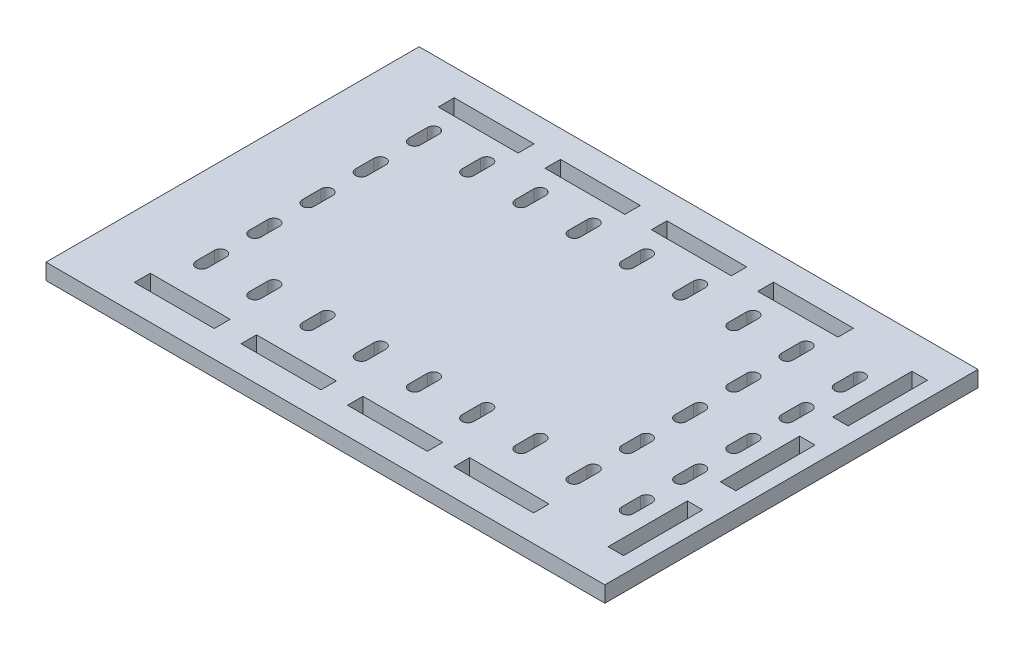
SolidWorks part; units mm, degrees
ref_plane "Front Plane" through (0, 0, 0) normal (0, 0, 1) x (1, 0, 0)
ref_plane "Top Plane" through (0, 0, 0) normal (0, 1, 0) x (1, 0, 0)
ref_plane "Right Plane" through (0, 0, 0) normal (1, 0, 0) x (0, 0, -1)
sketch "Sketch1" plane through (0, 0, 0) normal (0, 1, 0) x (1, 0, 0)
  line L1 (0, 0) -> (200, 0)
  line L2 (0, 0) -> (0, 140.2)
  line L3 (0, 140.2) -> (200, 140.2)
  line L4 (200, 0) -> (200, 140.2)
  line L5 (0, 0) -> (200, 140.2) construction
  line L6 (0, 140.2) -> (200, 0) construction
  point P4 (100, 70.1)
  dimension "D1" = 200
  dimension "D2" = 140.2
extrude "Boss-Extrude1" add sketch "Sketch1" along normal blind 6
sketch "Sketch2" plane through (0, 6, 0) normal (0, 1, 0) x (1, 0, 0)
  line L0 (188.2, 127.2) -> (194, 127.2)
  line L1 (188.2, 127.2) -> (188.2, 97.4)
  line L2 (188.2, 97.4) -> (194, 97.4)
  line L3 (194, 127.2) -> (194, 97.4)
  line L4 (188.2, 127.2) -> (194, 97.4) construction
  line L5 (188.2, 97.4) -> (194, 127.2) construction
  line L6 (188.2, 85) -> (194, 85)
  line L7 (188.2, 85) -> (188.2, 55.2)
  line L8 (188.2, 55.2) -> (194, 55.2)
  line L9 (194, 85) -> (194, 55.2)
  line L10 (188.2, 85) -> (194, 55.2) construction
  line L11 (188.2, 55.2) -> (194, 85) construction
  line L12 (188.2, 42.8) -> (194, 42.8)
  line L13 (188.2, 42.8) -> (188.2, 13)
  line L14 (188.2, 13) -> (194, 13)
  line L15 (194, 42.8) -> (194, 13)
  line L16 (188.2, 42.8) -> (194, 13) construction
  line L17 (188.2, 13) -> (194, 42.8) construction
  line L19 (200, 140.2) -> (0, 140.2) construction
  line L22 (0, 0) -> (200, 0) construction
  line L23 (200, 0) -> (200, 140.2) construction
  point P4 (191.1, 112.3)
  point P9 (191.1, 70.1)
  point P14 (191.1, 27.9)
  dimension "D1" = 13
  dimension "D2" = 29.8
  dimension "D3" = 29.8
  dimension "D4" = 13
  dimension "D5" = 0
  dimension "D6" = 12.4
  dimension "D7" = 0
  dimension "D8" = 29.8
  dimension "D9" = 12.4
  dimension "D10" = 6
  dimension "D11" = 5.8
  dimension "D12" = 5.8
  dimension "D13" = 5.8
extrude "Cut-Extrude1" cut sketch "Sketch2" against normal blind 6
sketch "Sketch5" plane through (0, 6, 0) normal (0, 1, 0) x (1, 0, 0)
  line L0 (53.2, 130.1) -> (83.2, 130.1)
  line L1 (133.2, 124.2) -> (163.2, 124.4)
  line L2 (163.2, 124.4) -> (163.2, 130.2)
  line L3 (163.2, 130.2) -> (133.2, 130.2)
  line L4 (133.2, 130.2) -> (133.2, 124.2)
  line L5 (93.2, 124.3) -> (123.2, 124.3)
  line L6 (123.2, 124.3) -> (123.2, 130.1)
  line L7 (123.2, 130.1) -> (93.2, 130.1)
  line L8 (93.2, 130.1) -> (93.2, 124.3)
  line L10 (83.2, 124.3) -> (83.2, 130.1)
  line L12 (53.2, 124.3) -> (53.2, 130.1)
  line L13 (13.2, 124.2) -> (43.2, 124.2)
  line L14 (43.2, 124.2) -> (43.2, 130.2)
  line L15 (43.2, 130.2) -> (13.2, 130.2)
  line L16 (13.2, 130.2) -> (13.2, 124.2)
  line L17 (148.2, 130.2) -> (188.2, 130.2) construction
  line L18 (188.2, 127.2) -> (188.2, 130.2)
  line L19 (83.2, 124.3) -> (53.2, 124.3)
  line L20 (200, 140.2) -> (0, 140.2) construction
  line L21 (53.2, 15.9) -> (83.2, 15.9)
  line L22 (200, 70.1) -> (0, 70.1) construction
  line L23 (200, 0) -> (200, 140.2) construction
  line L24 (0, 140.2) -> (0, 0) construction
  line L25 (13.2, 10) -> (13.2, 16)
  line L26 (43.2, 10) -> (13.2, 10)
  line L27 (43.2, 16) -> (43.2, 10)
  line L28 (13.2, 16) -> (43.2, 16)
  line L29 (53.2, 15.9) -> (53.2, 10.1)
  line L31 (83.2, 15.9) -> (83.2, 10.1)
  line L33 (93.2, 10.1) -> (93.2, 15.9)
  line L34 (123.2, 10.1) -> (93.2, 10.1)
  line L35 (123.2, 15.9) -> (123.2, 10.1)
  line L36 (93.2, 15.9) -> (123.2, 15.9)
  line L37 (133.2, 10) -> (133.2, 16)
  line L38 (163.2, 10) -> (133.2, 10)
  line L39 (163.2, 15.8) -> (163.2, 10)
  line L40 (133.2, 16) -> (163.2, 15.8)
  line L41 (83.2, 10.1) -> (53.2, 10.1)
  point P1 (83.2, 127.2)
  point P21 (133.2, 127.2)
  point P23 (123.2, 127.2)
  point P24 (93.2, 127.2)
  point P27 (53.2, 127.2)
  point P28 (43.2, 127.2)
  dimension "D2" = 30
  dimension "D3" = 30
  dimension "D4" = 30
  dimension "D5" = 30
  dimension "D6" = 10
  dimension "D7" = 10
  dimension "D8" = 10
  dimension "D9" = 40
  dimension "D10" = 13
  dimension "D11" = 13
  dimension "D12" = 5.8
  dimension "D13" = 5.8
  dimension "D14" = 5.8
  dimension "D15" = 6
  dimension "D16" = 13
  dimension "D17" = 13
  dimension "D18" = 5.8
  dimension "D19" = 13
  dimension "D20" = 5.8
extrude "Cut-Extrude3" cut sketch "Sketch5" against normal blind 6 contours L15 L16 L13 L14 | L19 L10 L0 L12 | L7 L8 L5 L6 | L3 L4 L1 L2 | L40 L37 L38 L39 | L36 L33 L34 L35 | L41 L31 L21 L29 | L28 L25 L26 L27
sketch "Sketch6" plane through (0, 6, 0) normal (0, 1, 0) x (1, 0, 0)
  line L0 (200, 0) -> (200, 140.2) construction
  line L2 (182.2, 68.5311) -> (182.2, 75.5311)
  line L3 (177.8, 68.5304) -> (177.8, 75.5304)
  line L4 (162.2, 68.5304) -> (162.2, 75.5304)
  line L5 (157.8, 68.5304) -> (157.8, 75.5304)
  line L6 (182.2, 48.5311) -> (182.2, 55.5311)
  line L7 (177.8, 48.5304) -> (177.8, 55.5304)
  line L8 (162.2, 48.5304) -> (162.2, 55.5304)
  line L9 (182.2, 88.5311) -> (182.2, 95.5311)
  line L10 (177.8, 88.5304) -> (177.8, 95.5304)
  line L11 (182.2, 108.531) -> (182.2, 115.531)
  line L12 (177.8, 108.5313) -> (177.8, 115.5313)
  line L13 (162.2, 108.5304) -> (162.2, 115.5304)
  line L14 (157.8, 108.5304) -> (157.8, 115.5304)
  line L15 (162.2, 88.5304) -> (162.2, 95.5304)
  line L16 (157.8, 88.5304) -> (157.8, 95.5304)
  line L17 (157.8, 48.5304) -> (157.8, 55.5304)
  line L18 (182.2, 28.5311) -> (182.2, 35.5311)
  line L19 (177.8, 28.5304) -> (177.8, 35.5304)
  line L20 (162.2, 28.5304) -> (162.2, 35.5304)
  line L21 (157.8, 28.5304) -> (157.8, 35.5304)
  line L24 (142.2, 108.5304) -> (142.2, 115.5304)
  line L25 (137.8, 108.5304) -> (137.8, 115.5304)
  line L29 (142.2, 28.5304) -> (142.2, 35.5304)
  line L30 (137.8, 28.5304) -> (137.8, 35.5304)
  line L34 (122.2, 108.5304) -> (122.2, 115.5304)
  line L35 (117.8, 108.5304) -> (117.8, 115.5304)
  line L39 (122.2, 28.5304) -> (122.2, 35.5304)
  line L40 (117.8, 28.5304) -> (117.8, 35.5304)
  line L44 (102.2, 108.5304) -> (102.2, 115.5304)
  line L45 (97.8, 108.5304) -> (97.8, 115.5304)
  line L49 (102.2, 28.5304) -> (102.2, 35.5304)
  line L50 (97.8, 28.5304) -> (97.8, 35.5304)
  line L54 (82.2, 108.5304) -> (82.2, 115.5304)
  line L55 (77.8, 108.5304) -> (77.8, 115.5304)
  line L59 (82.2, 28.5304) -> (82.2, 35.5304)
  line L60 (77.8, 28.5304) -> (77.8, 35.5304)
  line L64 (62.2, 108.5304) -> (62.2, 115.5304)
  line L65 (57.8, 108.5304) -> (57.8, 115.5304)
  line L69 (62.2, 28.5304) -> (62.2, 35.5304)
  line L70 (57.8, 28.5304) -> (57.8, 35.5304)
  line L74 (42.2, 108.5304) -> (42.2, 115.5304)
  line L75 (37.8, 108.5304) -> (37.8, 115.5304)
  line L79 (42.2, 28.5304) -> (42.2, 35.5304)
  line L80 (37.8, 28.5304) -> (37.8, 35.5304)
  line L81 (22.2, 68.5304) -> (22.2, 75.5304)
  line L82 (17.8, 68.5304) -> (17.8, 75.5304)
  line L83 (22.2, 48.5304) -> (22.2, 55.5304)
  line L84 (22.2, 108.5304) -> (22.2, 115.5304)
  line L85 (17.8, 108.5304) -> (17.8, 115.5304)
  line L86 (22.2, 88.5304) -> (22.2, 95.5304)
  line L87 (17.8, 88.5304) -> (17.8, 95.5304)
  line L88 (17.8, 48.5304) -> (17.8, 55.5304)
  line L89 (22.2, 28.5304) -> (22.2, 35.5304)
  line L90 (17.8, 28.5304) -> (17.8, 35.5304)
  line L91 (142.2, 68.5304) -> (142.2, 75.5304) [skipped]
  line L92 (137.8, 68.5304) -> (137.8, 75.5304) [skipped]
  line L93 (142.2, 48.5304) -> (142.2, 55.5304) [skipped]
  line L94 (142.2, 88.5304) -> (142.2, 95.5304) [skipped]
  line L95 (137.8, 88.5304) -> (137.8, 95.5304) [skipped]
  line L96 (137.8, 48.5304) -> (137.8, 55.5304) [skipped]
  line L97 (122.2, 68.5304) -> (122.2, 75.5304) [skipped]
  line L98 (117.8, 68.5304) -> (117.8, 75.5304) [skipped]
  line L99 (122.2, 48.5304) -> (122.2, 55.5304) [skipped]
  line L100 (122.2, 88.5304) -> (122.2, 95.5304) [skipped]
  line L101 (117.8, 88.5304) -> (117.8, 95.5304) [skipped]
  line L102 (117.8, 48.5304) -> (117.8, 55.5304) [skipped]
  line L103 (102.2, 68.5304) -> (102.2, 75.5304) [skipped]
  line L104 (97.8, 68.5304) -> (97.8, 75.5304) [skipped]
  line L105 (102.2, 48.5304) -> (102.2, 55.5304) [skipped]
  line L106 (102.2, 88.5304) -> (102.2, 95.5304) [skipped]
  line L107 (97.8, 88.5304) -> (97.8, 95.5304) [skipped]
  line L108 (97.8, 48.5304) -> (97.8, 55.5304) [skipped]
  line L109 (82.2, 68.5304) -> (82.2, 75.5304) [skipped]
  line L110 (77.8, 68.5304) -> (77.8, 75.5304) [skipped]
  line L111 (82.2, 48.5304) -> (82.2, 55.5304) [skipped]
  line L112 (82.2, 88.5304) -> (82.2, 95.5304) [skipped]
  line L113 (77.8, 88.5304) -> (77.8, 95.5304) [skipped]
  line L114 (77.8, 48.5304) -> (77.8, 55.5304) [skipped]
  line L115 (62.2, 68.5304) -> (62.2, 75.5304) [skipped]
  line L116 (57.8, 68.5304) -> (57.8, 75.5304) [skipped]
  line L117 (62.2, 48.5304) -> (62.2, 55.5304) [skipped]
  line L118 (62.2, 88.5304) -> (62.2, 95.5304) [skipped]
  line L119 (57.8, 88.5304) -> (57.8, 95.5304) [skipped]
  line L120 (57.8, 48.5304) -> (57.8, 55.5304) [skipped]
  line L121 (42.2, 68.5304) -> (42.2, 75.5304) [skipped]
  line L122 (37.8, 68.5304) -> (37.8, 75.5304) [skipped]
  line L123 (42.2, 48.5304) -> (42.2, 55.5304) [skipped]
  line L124 (42.2, 88.5304) -> (42.2, 95.5304) [skipped]
  line L125 (37.8, 88.5304) -> (37.8, 95.5304) [skipped]
  line L126 (37.8, 48.5304) -> (37.8, 55.5304) [skipped]
  arc A0 (177.8, 68.5304) -> (182.2, 68.5311) centre (180, 68.5308) ccw
  arc A1 (182.2, 75.5311) -> (177.8, 75.5304) centre (180, 75.5311) ccw
  arc A2 (157.8, 68.5304) -> (162.2, 68.5304) centre (160, 68.5304) ccw
  arc A3 (162.2, 75.5304) -> (157.8, 75.5304) centre (160, 75.5304) ccw
  arc A4 (177.8, 48.5304) -> (182.2, 48.5311) centre (180, 48.5308) ccw
  arc A5 (182.2, 55.5311) -> (177.8, 55.5304) centre (180, 55.5311) ccw
  arc A6 (157.8, 48.5304) -> (162.2, 48.5304) centre (160, 48.5304) ccw
  arc A7 (162.2, 55.5304) -> (157.8, 55.5304) centre (160, 55.5304) ccw
  arc A8 (177.8, 88.5304) -> (182.2, 88.5311) centre (180, 88.5308) ccw
  arc A9 (182.2, 95.5311) -> (177.8, 95.5304) centre (180, 95.5311) ccw
  arc A10 (177.8, 108.5313) -> (182.2, 108.531) centre (180, 108.5311) ccw
  arc A11 (182.2, 115.531) -> (177.8, 115.5313) centre (180, 115.531) ccw
  arc A12 (162.2, 115.5304) -> (157.8, 115.5304) centre (160, 115.5304) ccw
  arc A13 (157.8, 108.5304) -> (162.2, 108.5304) centre (160, 108.5304) ccw
  arc A14 (157.8, 88.5304) -> (162.2, 88.5304) centre (160, 88.5304) ccw
  arc A15 (162.2, 95.5304) -> (157.8, 95.5304) centre (160, 95.5304) ccw
  arc A16 (177.8, 28.5304) -> (182.2, 28.5311) centre (180, 28.5308) ccw
  arc A17 (182.2, 35.5311) -> (177.8, 35.5304) centre (180, 35.5311) ccw
  arc A18 (157.8, 28.5304) -> (162.2, 28.5304) centre (160, 28.5304) ccw
  arc A19 (162.2, 35.5304) -> (157.8, 35.5304) centre (160, 35.5304) ccw
  arc A24 (142.2, 115.5304) -> (137.8, 115.5304) centre (140, 115.5304) ccw
  arc A25 (137.8, 108.5304) -> (142.2, 108.5304) centre (140, 108.5304) ccw
  arc A28 (137.8, 28.5304) -> (142.2, 28.5304) centre (140, 28.5304) ccw
  arc A29 (142.2, 35.5304) -> (137.8, 35.5304) centre (140, 35.5304) ccw
  arc A34 (122.2, 115.5304) -> (117.8, 115.5304) centre (120, 115.5304) ccw
  arc A35 (117.8, 108.5304) -> (122.2, 108.5304) centre (120, 108.5304) ccw
  arc A38 (117.8, 28.5304) -> (122.2, 28.5304) centre (120, 28.5304) ccw
  arc A39 (122.2, 35.5304) -> (117.8, 35.5304) centre (120, 35.5304) ccw
  arc A44 (102.2, 115.5304) -> (97.8, 115.5304) centre (100, 115.5304) ccw
  arc A45 (97.8, 108.5304) -> (102.2, 108.5304) centre (100, 108.5304) ccw
  arc A48 (97.8, 28.5304) -> (102.2, 28.5304) centre (100, 28.5304) ccw
  arc A49 (102.2, 35.5304) -> (97.8, 35.5304) centre (100, 35.5304) ccw
  arc A54 (82.2, 115.5304) -> (77.8, 115.5304) centre (80, 115.5304) ccw
  arc A55 (77.8, 108.5304) -> (82.2, 108.5304) centre (80, 108.5304) ccw
  arc A58 (77.8, 28.5304) -> (82.2, 28.5304) centre (80, 28.5304) ccw
  arc A59 (82.2, 35.5304) -> (77.8, 35.5304) centre (80, 35.5304) ccw
  arc A64 (62.2, 115.5304) -> (57.8, 115.5304) centre (60, 115.5304) ccw
  arc A65 (57.8, 108.5304) -> (62.2, 108.5304) centre (60, 108.5304) ccw
  arc A68 (57.8, 28.5304) -> (62.2, 28.5304) centre (60, 28.5304) ccw
  arc A69 (62.2, 35.5304) -> (57.8, 35.5304) centre (60, 35.5304) ccw
  arc A74 (42.2, 115.5304) -> (37.8, 115.5304) centre (40, 115.5304) ccw
  arc A75 (37.8, 108.5304) -> (42.2, 108.5304) centre (40, 108.5304) ccw
  arc A78 (37.8, 28.5304) -> (42.2, 28.5304) centre (40, 28.5304) ccw
  arc A79 (42.2, 35.5304) -> (37.8, 35.5304) centre (40, 35.5304) ccw
  arc A80 (17.8, 68.5304) -> (22.2, 68.5304) centre (20, 68.5304) ccw
  arc A81 (22.2, 75.5304) -> (17.8, 75.5304) centre (20, 75.5304) ccw
  arc A82 (17.8, 48.5304) -> (22.2, 48.5304) centre (20, 48.5304) ccw
  arc A83 (22.2, 55.5304) -> (17.8, 55.5304) centre (20, 55.5304) ccw
  arc A84 (22.2, 115.5304) -> (17.8, 115.5304) centre (20, 115.5304) ccw
  arc A85 (17.8, 108.5304) -> (22.2, 108.5304) centre (20, 108.5304) ccw
  arc A86 (17.8, 88.5304) -> (22.2, 88.5304) centre (20, 88.5304) ccw
  arc A87 (22.2, 95.5304) -> (17.8, 95.5304) centre (20, 95.5304) ccw
  arc A88 (17.8, 28.5304) -> (22.2, 28.5304) centre (20, 28.5304) ccw
  arc A89 (22.2, 35.5304) -> (17.8, 35.5304) centre (20, 35.5304) ccw
  arc A90 (137.8, 68.5304) -> (142.2, 68.5304) centre (140, 68.5304) ccw [skipped]
  arc A91 (142.2, 75.5304) -> (137.8, 75.5304) centre (140, 75.5304) ccw [skipped]
  arc A92 (137.8, 48.5304) -> (142.2, 48.5304) centre (140, 48.5304) ccw [skipped]
  arc A93 (142.2, 55.5304) -> (137.8, 55.5304) centre (140, 55.5304) ccw [skipped]
  arc A94 (137.8, 88.5304) -> (142.2, 88.5304) centre (140, 88.5304) ccw [skipped]
  arc A95 (142.2, 95.5304) -> (137.8, 95.5304) centre (140, 95.5304) ccw [skipped]
  arc A96 (117.8, 68.5304) -> (122.2, 68.5304) centre (120, 68.5304) ccw [skipped]
  arc A97 (122.2, 75.5304) -> (117.8, 75.5304) centre (120, 75.5304) ccw [skipped]
  arc A98 (117.8, 48.5304) -> (122.2, 48.5304) centre (120, 48.5304) ccw [skipped]
  arc A99 (122.2, 55.5304) -> (117.8, 55.5304) centre (120, 55.5304) ccw [skipped]
  arc A100 (117.8, 88.5304) -> (122.2, 88.5304) centre (120, 88.5304) ccw [skipped]
  arc A101 (122.2, 95.5304) -> (117.8, 95.5304) centre (120, 95.5304) ccw [skipped]
  arc A102 (97.8, 68.5304) -> (102.2, 68.5304) centre (100, 68.5304) ccw [skipped]
  arc A103 (102.2, 75.5304) -> (97.8, 75.5304) centre (100, 75.5304) ccw [skipped]
  arc A104 (97.8, 48.5304) -> (102.2, 48.5304) centre (100, 48.5304) ccw [skipped]
  arc A105 (102.2, 55.5304) -> (97.8, 55.5304) centre (100, 55.5304) ccw [skipped]
  arc A106 (97.8, 88.5304) -> (102.2, 88.5304) centre (100, 88.5304) ccw [skipped]
  arc A107 (102.2, 95.5304) -> (97.8, 95.5304) centre (100, 95.5304) ccw [skipped]
  arc A108 (77.8, 68.5304) -> (82.2, 68.5304) centre (80, 68.5304) ccw [skipped]
  arc A109 (82.2, 75.5304) -> (77.8, 75.5304) centre (80, 75.5304) ccw [skipped]
  arc A110 (77.8, 48.5304) -> (82.2, 48.5304) centre (80, 48.5304) ccw [skipped]
  arc A111 (82.2, 55.5304) -> (77.8, 55.5304) centre (80, 55.5304) ccw [skipped]
  arc A112 (77.8, 88.5304) -> (82.2, 88.5304) centre (80, 88.5304) ccw [skipped]
  arc A113 (82.2, 95.5304) -> (77.8, 95.5304) centre (80, 95.5304) ccw [skipped]
  arc A114 (57.8, 68.5304) -> (62.2, 68.5304) centre (60, 68.5304) ccw [skipped]
  arc A115 (62.2, 75.5304) -> (57.8, 75.5304) centre (60, 75.5304) ccw [skipped]
  arc A116 (57.8, 48.5304) -> (62.2, 48.5304) centre (60, 48.5304) ccw [skipped]
  arc A117 (62.2, 55.5304) -> (57.8, 55.5304) centre (60, 55.5304) ccw [skipped]
  arc A118 (57.8, 88.5304) -> (62.2, 88.5304) centre (60, 88.5304) ccw [skipped]
  arc A119 (62.2, 95.5304) -> (57.8, 95.5304) centre (60, 95.5304) ccw [skipped]
  arc A120 (37.8, 68.5304) -> (42.2, 68.5304) centre (40, 68.5304) ccw [skipped]
  arc A121 (42.2, 75.5304) -> (37.8, 75.5304) centre (40, 75.5304) ccw [skipped]
  arc A122 (37.8, 48.5304) -> (42.2, 48.5304) centre (40, 48.5304) ccw [skipped]
  arc A123 (42.2, 55.5304) -> (37.8, 55.5304) centre (40, 55.5304) ccw [skipped]
  arc A124 (37.8, 88.5304) -> (42.2, 88.5304) centre (40, 88.5304) ccw [skipped]
  arc A125 (42.2, 95.5304) -> (37.8, 95.5304) centre (40, 95.5304) ccw [skipped]
  point P4 (177.8, 72.0304)
  point P64 (162.2, 72.0304)
  dimension "D7" = 2.2
  dimension "D8" = 2.2
  dimension "D9" = 2.2
  dimension "D10" = 2.2
  dimension "D11" = 2.2
  dimension "D12" = 2.2
  dimension "D13" = 2.2
  dimension "D14" = 2.2
  dimension "D19" = 4.4
  dimension "D1" = 13
  dimension "D2" = 13
  dimension "D3" = 17.8
  dimension "D4" = 4.4
  dimension "D5" = 4.4
  dimension "D6" = 4.4
  dimension "D15" = 15.6
  dimension "D16" = 15.6
  dimension "D17" = 17.8
  dimension "D20" = 7
  dimension "D21" = 7
  dimension "D22" = 7
  dimension "D23" = 7
  dimension "D25" = 7
  dimension "D26" = 7
  dimension "D27" = 7
  dimension "D18" = 4
  dimension "D29" = 8
extrude "Cut-Extrude4" cut sketch "Sketch6" against normal blind 6
sketch "Sketch7" plane through (0, 0, 0) normal (-1, 0, 0) x (0, 0, 1)
  line L1 (-140.2, 0) -> (0, 0)
  line L2 (-140.2, 0) -> (-140.2, 6)
  line L3 (-140.2, 6) -> (0, 6)
  line L4 (0, 0) -> (0, 6)
  line L5 (-140.2, 0) -> (0, 6) construction
  line L6 (-140.2, 6) -> (0, 0) construction
  point P4 (-70.1, 3)
extrude "Boss-Extrude2" add sketch "Sketch7" along normal blind 10
